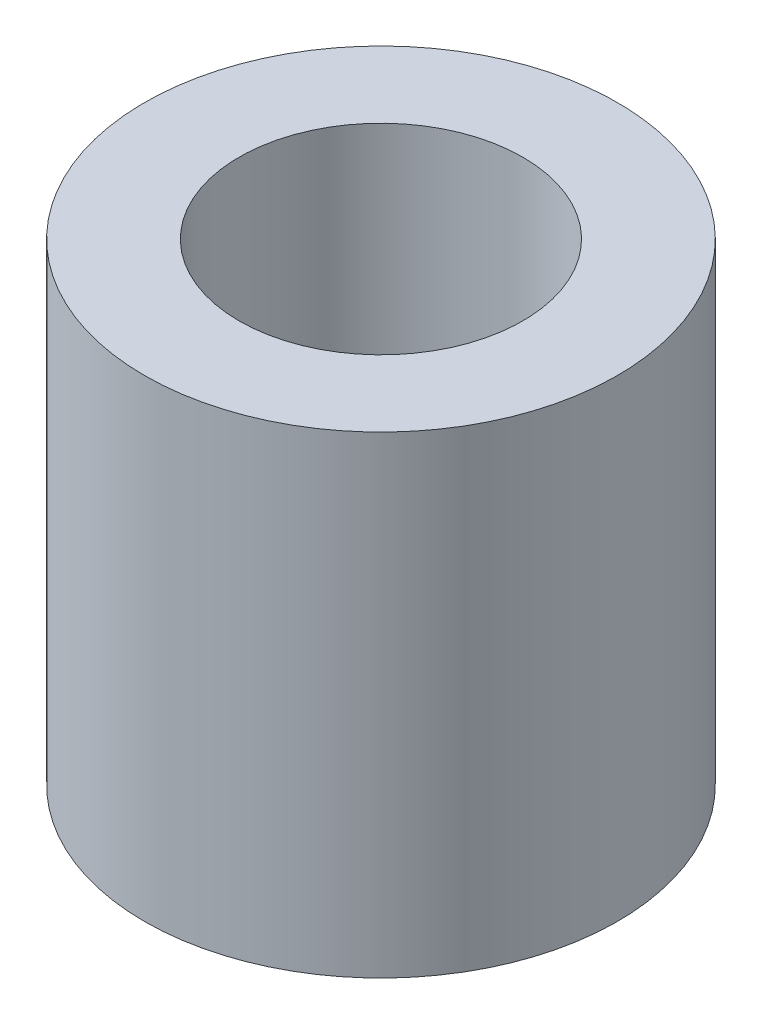
SolidWorks part; units mm, degrees
ref_plane "Plan de face" through (0, 0, 0) normal (0, 0, 1) x (1, 0, 0)
ref_plane "Plan de dessus" through (0, 0, 0) normal (0, 1, 0) x (1, 0, 0)
ref_plane "Plan de droite" through (0, 0, 0) normal (1, 0, 0) x (0, 0, -1)
sketch "Esquisse1" plane through (0, 0, 0) normal (0, 1, 0) x (1, 0, 0)
  circle A0 centre (0, 0) radius 1.5
  circle A1 centre (0, 0) radius 2.5
  dimension "D1" = 3
  dimension "D2" = 1
extrude "Boss.-Extru.1" add sketch "Esquisse1" along normal blind 5
sketch "Esquisse2" plane through (0, 0, 0) normal (1, 0, 0) x (0, 0, -1)
  line L0 (0, 5) -> (0, 0) construction
  line L1 (2.5, 5) -> (-2.5, 5) construction
